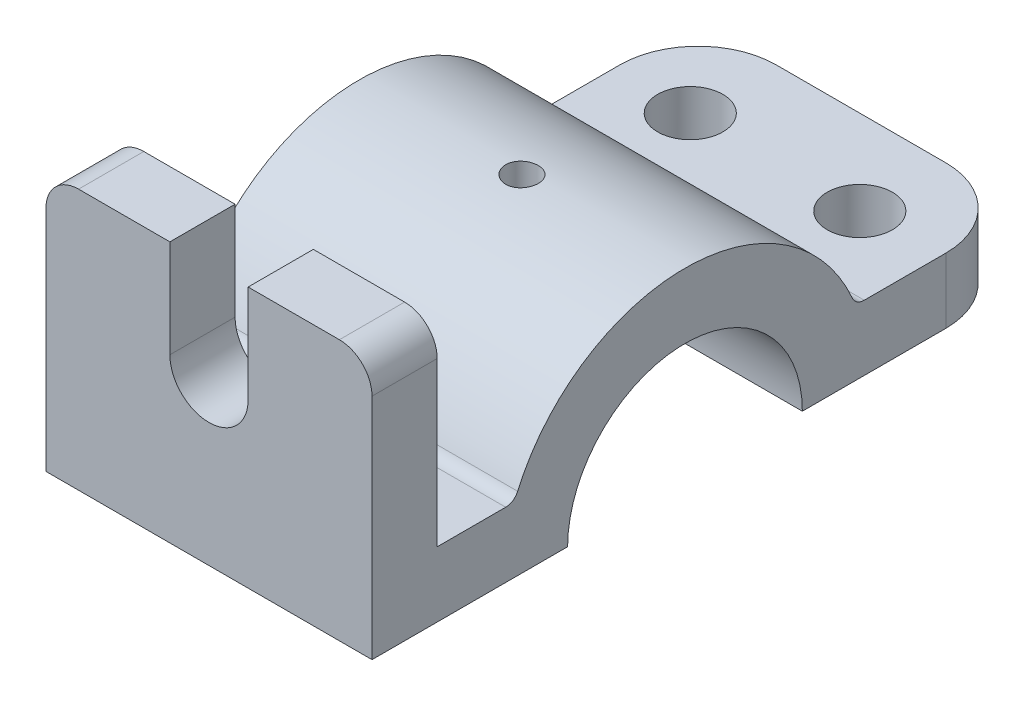
SolidWorks part; units mm, degrees
ref_plane "Ön Düzlem" through (0, 0, 0) normal (0, 0, 1) x (1, 0, 0)
ref_plane "Üst Düzlem" through (0, 0, 0) normal (0, 1, 0) x (1, 0, 0)
ref_plane "Sağ Düzlem" through (0, 0, 0) normal (1, 0, 0) x (0, 0, -1)
sketch "Çizim2" plane through (0, 0, 0) normal (1, 0, 0) x (0, 0, -1)
  line L0 (-18, 0) -> (-48, 0)
  line L1 (-48, 0) -> (-48, 40)
  line L2 (-48, 40) -> (-38, 40)
  line L3 (-38, 40) -> (-38, 10)
  line L4 (-38, 10) -> (-26.1534, 10)
  line L5 (28, 0) -> (52, 0)
  line L6 (52, 0) -> (52, 10)
  line L7 (52, 10) -> (26.1534, 10)
  line L8 (18, 0) -> (28, 0)
  arc A0 (18, 0) -> (-18, 0) centre (0, 0) ccw
  arc A1 (26.1534, 10) -> (-26.1534, 10) centre (0, 0) ccw
  dimension "D1" = 36
  dimension "D2" = 56
  dimension "D3" = 10
  dimension "D4" = 10
  dimension "D5" = 100
  dimension "D6" = 30
  dimension "D7" = 40
extrude "Yükseklik-Ekstrüzyon1" add sketch "Çizim2" against normal blind 50
fillet "Radyus1" radius 5 2 edges at (-50, 40, 43) (0, 40, 43)
sketch "Çizim3" plane through (0, 0, 48) normal (0, 0, 1) x (1, 0, 0)
  line L0 (-31, 40) -> (-31, 25)
  line L1 (-45, 40) -> (-5, 40) construction
  line L2 (-50, 0) -> (0, 0) construction
  line L3 (-19, 25) -> (-19, 40)
  line L4 (-50, 35) -> (-50, 0) construction
  line L5 (-31, 40) -> (-19, 40)
  arc A0 (-31, 25) -> (-19, 25) centre (-25, 25) ccw
  dimension "D1" = 25
  dimension "D2" = 12
  dimension "D3" = 25
extrude "Kes-Ekstrüzyon1" cut sketch "Çizim3" against normal up to surface (10 mm away) up to face at (-25, 28.6785, 38)
ref_plane "Düzlem1" through (0, 28, 0) normal (0, 1, 0) x (1, 0, 0)
sketch "Çizim4" plane through (0, 28, 0) normal (0, 1, 0) x (1, 0, 0)
  circle A0 centre (-25, 0) radius 2.5
  dimension "D1" = 5
extrude "Kes-Ekstrüzyon2" cut sketch "Çizim4" against normal up to surface (10.1745 mm away)
sketch "Çizim5" plane through (0, 10, 0) normal (0, 1, 0) x (1, 0, 0)
  line L0 (-50, 52) -> (0, 52) construction
  circle A0 centre (-38.1893, 39) radius 5
  circle A1 centre (-12.1893, 39) radius 5
  point P6 (-25, 52)
  dimension "D3" = 10
  dimension "D1" = 26
  dimension "D2" = 13
extrude "Kes-Ekstrüzyon3" cut sketch "Çizim5" against normal blind 26 contours A1 | A0
fillet "Radyus2" radius 12 2 edges at (-50, 5, -52) (0, 5, -52)
fillet "Radyus3" radius 2 2 edges at (-25, 10, -26.1534) (-25, 10, 26.1534)
